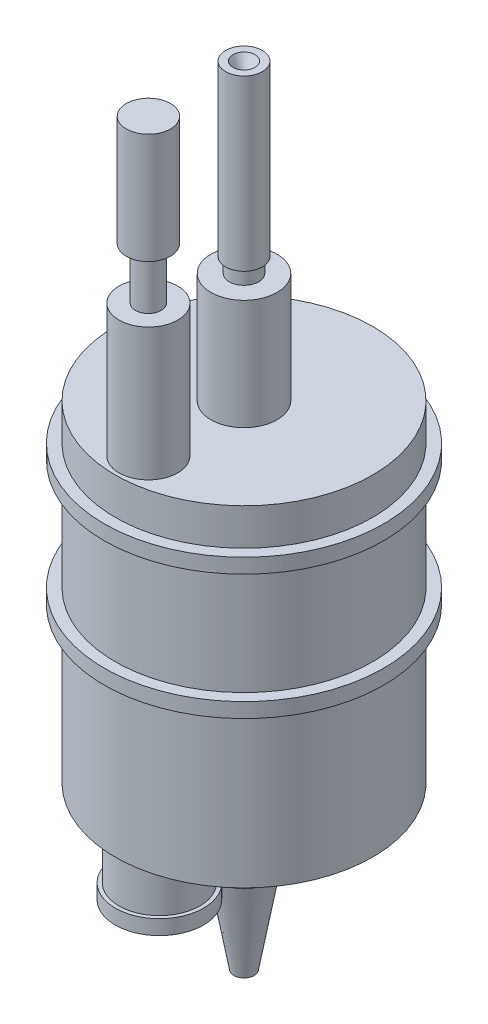
SolidWorks part; units mm, degrees
ref_plane "Front Plane" through (0, 0, 0) normal (0, 0, 1) x (1, 0, 0)
ref_plane "Top Plane" through (0, 0, 0) normal (0, 1, 0) x (1, 0, 0)
ref_plane "Right Plane" through (0, 0, 0) normal (1, 0, 0) x (0, 0, -1)
sketch "Sketch1" plane through (0, 0, 0) normal (0, 1, 0) x (1, 0, 0)
  circle A0 centre (0, 0) radius 17.5
  dimension "D1" = 35
extrude "Extrude1" add sketch "Sketch1" along normal blind 45
sketch "Sketch2" plane through (0, 0, 0) normal (0, -1, 0) x (1, 0, 0)
  line L0 (0, 11.5) -> (0, 0) construction
  circle A0 centre (0, 0) radius 3.5
  circle A1 centre (0, 11.5) radius 5.5
  circle A3 centre (0, 11.5) radius 6 construction
  circle A4 centre (0, 0) radius 17.5 construction
  dimension "D1" = 11
  dimension "D2" = 7
  dimension "D3" = 12
extrude "Extrude2" add sketch "Sketch2" along normal blind 8
sketch "Sketch3" plane through (0, -8, 0) normal (0, -1, 0) x (1, 0, 0)
  circle A0 centre (0, 0) radius 2.5
  dimension "D1" = 5
extrude "Extrude3" add sketch "Sketch3" along normal blind 2
sketch "Sketch4" plane through (0, -10, 0) normal (0, -1, 0) x (1, 0, 0)
  circle A0 centre (0, 0) radius 3.5
  circle A1 centre (0, 0) radius 3.5 construction
extrude "Extrude4" add sketch "Sketch4" along normal blind 12 draft 10 separate body
sketch "Sketch5" plane through (0, -8, 0) normal (0, -1, 0) x (1, 0, 0)
  circle A0 centre (0, 11.5) radius 6
  dimension "D1" = 12
extrude "Extrude6" add sketch "Sketch5" against normal blind 2
sketch "Sketch6" plane through (0, 45, 0) normal (0, 1, 0) x (1, 0, 0)
  circle A0 centre (0, 0) radius 4.5
  dimension "D1" = 9
extrude "Extrude7" add sketch "Sketch6" along normal blind 15
sketch "Sketch7" plane through (0, 60, 0) normal (0, 1, 0) x (1, 0, 0)
  circle A0 centre (0, 0) radius 2
  dimension "D1" = 4
extrude "Extrude8" add sketch "Sketch7" along normal blind 2
sketch "Sketch8" plane through (0, 62, 0) normal (0, 1, 0) x (1, 0, 0)
  circle A0 centre (0, 0) radius 2.5
  dimension "D1" = 5
extrude "Extrude9" add sketch "Sketch8" along normal blind 23
sketch "Sketch9" plane through (0, 45, 0) normal (0, 1, 0) x (1, 0, 0)
  line L0 (0, -13) -> (0, 0) construction
  circle A0 centre (0, -13) radius 4
  dimension "D1" = 8
  dimension "D2" = 13
extrude "Extrude10" add sketch "Sketch9" along normal blind 18
sketch "Sketch11" plane through (0, 63, 0) normal (0, 1, 0) x (1, 0, 0)
  circle A0 centre (0, -13) radius 1.75
  circle A2 centre (0, -13) radius 4 construction
  dimension "D1" = 3.5
extrude "Extrude11" add sketch "Sketch11" along normal blind 7
sketch "Sketch12" plane through (0, 70, 0) normal (0, 1, 0) x (1, 0, 0)
  circle A0 centre (0, -13) radius 3
  dimension "D1" = 6
extrude "Extrude12" add sketch "Sketch12" along normal blind 15
ref_plane "Plane1" through (0, 40, 0) normal (0, 1, 0) x (-1, 0, 0)
sketch "Sketch14" plane through (0, 40, 0) normal (0, 1, 0) x (-1, 0, 0)
  circle A0 centre (0, 0) radius 19
  dimension "D1" = 38
extrude "Boss-Extrude1" add sketch "Sketch14" against normal blind 2
ref_plane "Plane2" through (0, 23, 0) normal (0, -1, 0) x (1, 0, 0)
sketch "Sketch15" plane through (0, 23, 0) normal (0, -1, 0) x (1, 0, 0)
  circle A0 centre (0, 0) radius 19 construction
  circle A1 centre (0, 0) radius 19
extrude "Boss-Extrude2" add sketch "Sketch15" along normal blind 2
sketch "Sketch13" plane through (0, -22, 0) normal (0, -1, 0) x (1, 0, 0)
  circle A0 centre (0, 0) radius 0.6
  dimension "D1" = 1.2
extrude "Cut-Extrude1" cut sketch "Sketch13" against normal through all
sketch "Sketch16" plane through (0, 85, 0) normal (0, 1, 0) x (1, 0, 0)
  circle A0 centre (0, 0) radius 1.5
  dimension "D1" = 3
extrude "Cut-Extrude2" cut sketch "Sketch16" against normal blind 10 draft 30
